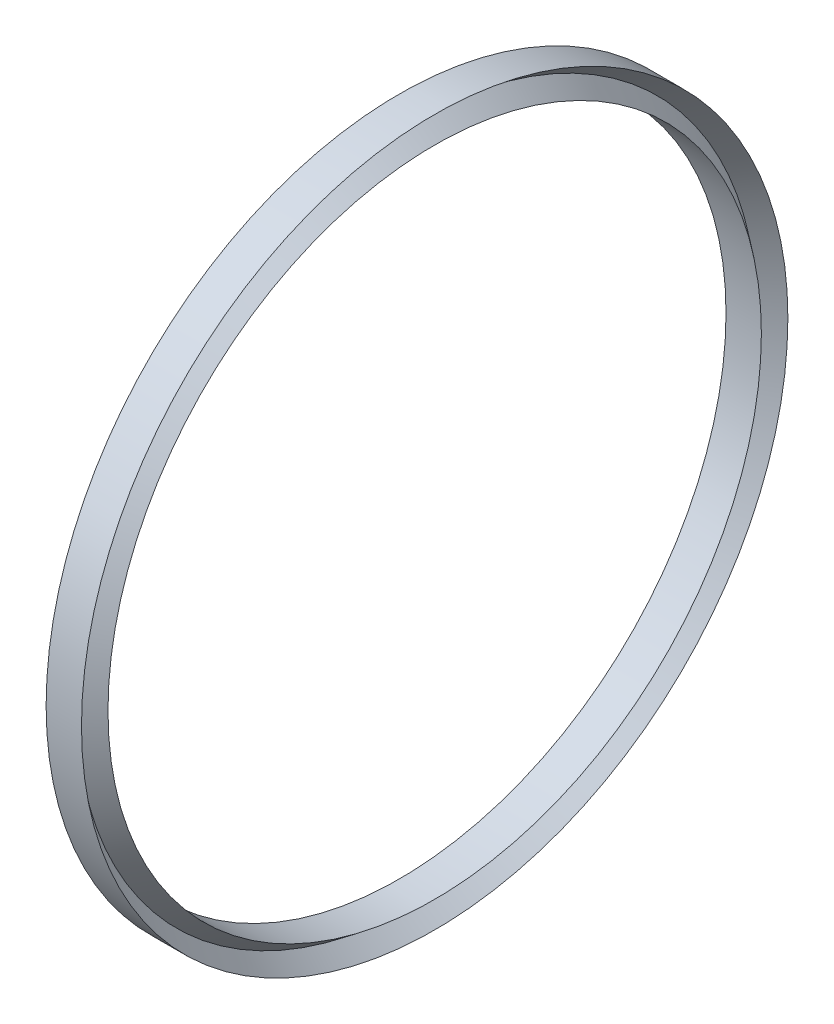
SolidWorks part; units mm, degrees
material "PP Copolymer"
ref_plane "Ön Düzlem" through (0, 0, 0) normal (0, 0, 1) x (1, 0, 0)
ref_plane "Üst Düzlem" through (0, 0, 0) normal (0, 1, 0) x (1, 0, 0)
ref_plane "Sağ Düzlem" through (0, 0, 0) normal (1, 0, 0) x (0, 0, -1)
sketch "Sketch1" plane through (0, 0, 0) normal (0, 0, 1) x (1, 0, 0)
  line L0 (-81.5782, 0) -> (80.7597, 0) construction
  line L1 (-67.8331, -40) -> (-63.8331, -40)
  line L2 (-63.8331, -37) -> (-67.8331, -37)
  line L3 (-67.8331, -37) -> (-67.8331, -40)
  line L4 (-67.8331, -37) -> (-63.8331, -40) construction
  line L5 (-67.8331, -40) -> (-63.8331, -37) construction
  line L6 (-63.8331, -37) -> (-65.8331, -38.5)
  line L7 (-65.8331, -38.5) -> (-63.8331, -40)
  point P8 (-65.8331, -38.5)
  dimension "D5" = 4
  dimension "D6" = 4
  dimension "D1" = 40
  dimension "D2" = 37
revolve "Revolve-Thin4" add sketch "Sketch1" angle 360 about L0
